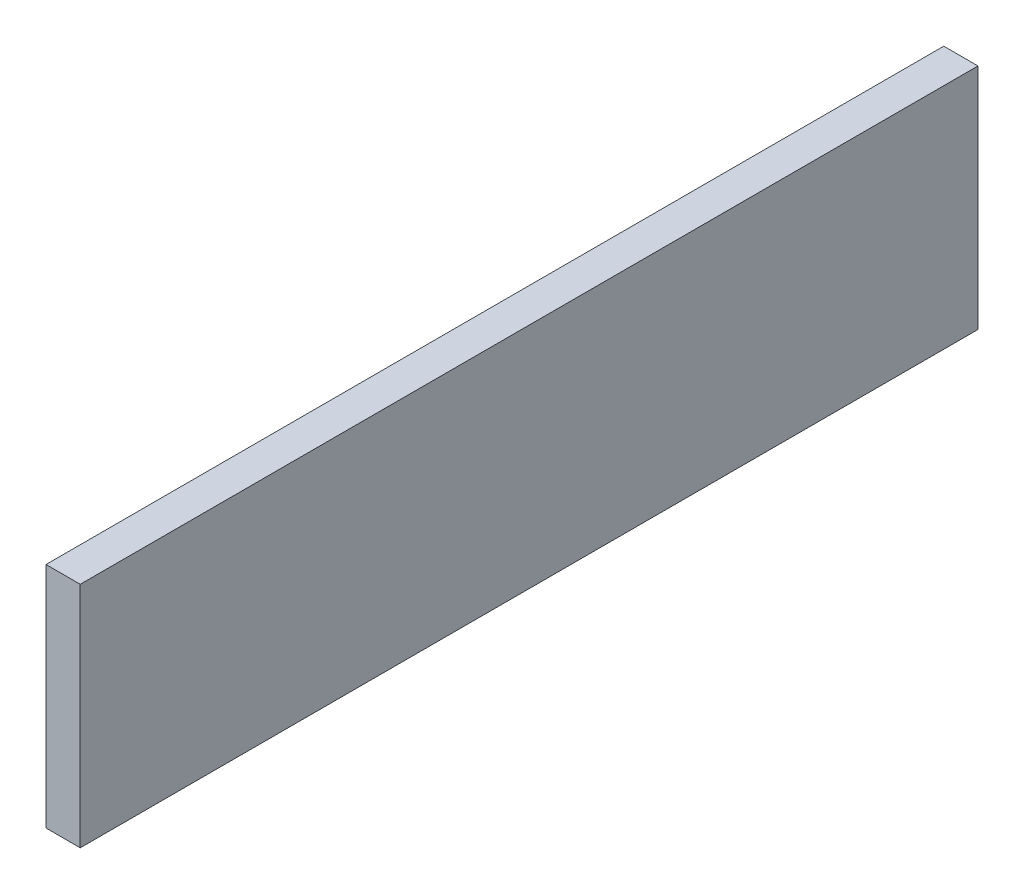
SolidWorks part; units mm, degrees
ref_plane "Front Plane" through (0, 0, 0) normal (0, 0, 1) x (1, 0, 0)
ref_plane "Top Plane" through (0, 0, 0) normal (0, 1, 0) x (1, 0, 0)
ref_plane "Right Plane" through (0, 0, 0) normal (1, 0, 0) x (0, 0, -1)
sketch "Sketch1" plane through (0, 0, 0) normal (1, 0, 0) x (0, 0, -1)
  line L1 (0, 0) -> (472, 0)
  line L2 (0, 0) -> (0, 120)
  line L3 (0, 120) -> (472, 120)
  line L4 (472, 0) -> (472, 120)
  dimension "D1" = 472
  dimension "D2" = 120
extrude "Boss-Extrude1" add sketch "Sketch1" along normal blind 18
